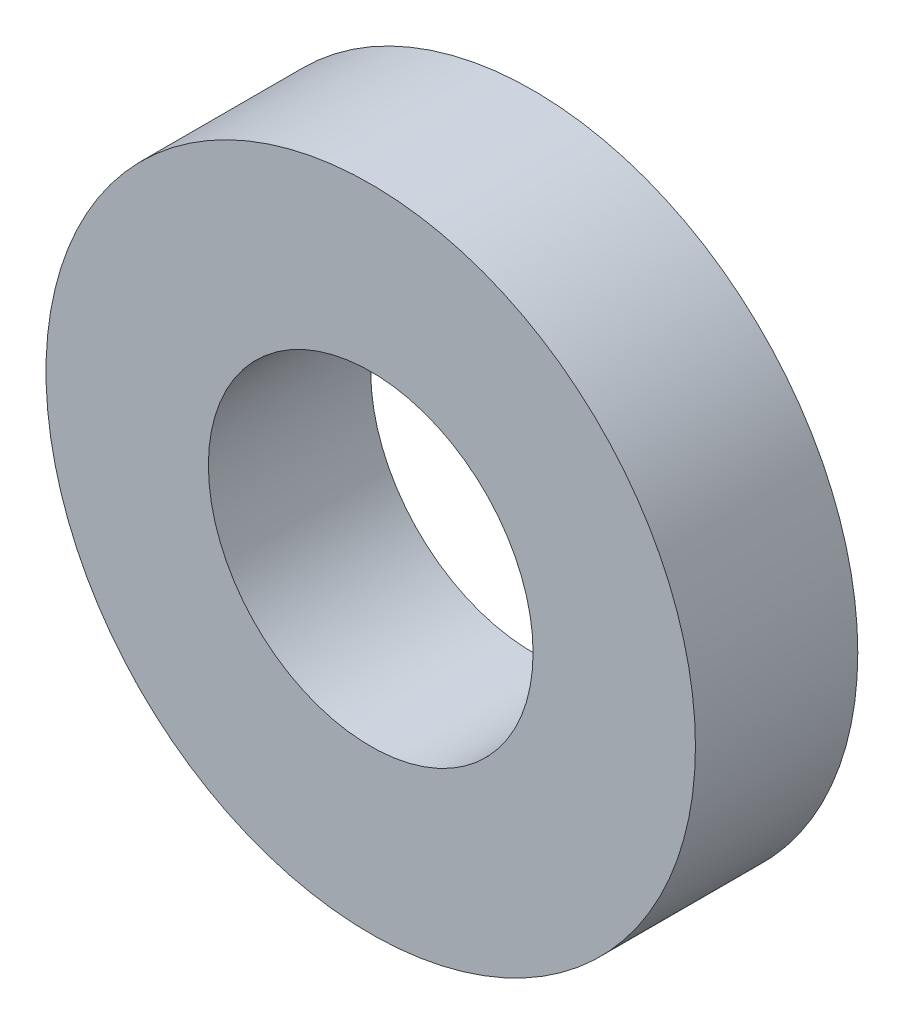
SolidWorks part; units mm, degrees
ref_plane "Front Plane" through (0, 0, 0) normal (0, 0, 1) x (1, 0, 0)
ref_plane "Top Plane" through (0, 0, 0) normal (0, 1, 0) x (1, 0, 0)
ref_plane "Right Plane" through (0, 0, 0) normal (1, 0, 0) x (0, 0, -1)
sketch "Sketch1" plane through (0, 0, 0) normal (0, 0, 1) x (1, 0, 0)
  circle A0 centre (0, 0) radius 3
  circle A1 centre (0, 0) radius 1.5
  dimension "D1" = 3
  dimension "D2" = 6
extrude "Boss-Extrude1" add sketch "Sketch1" along normal blind 1.5
